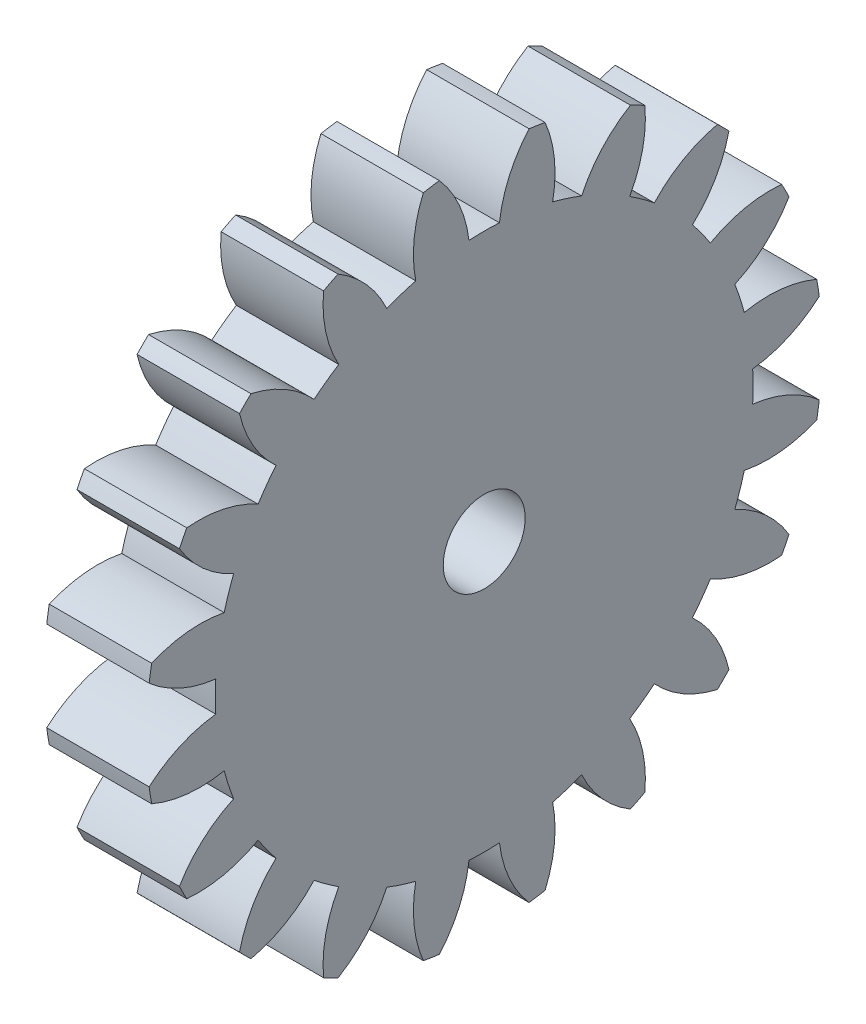
SolidWorks part; units mm, degrees
ref_plane "Plane1" through (0, 0, 0) normal (0, 0, 1) x (1, 0, 0)
ref_plane "Plane2" through (0, 0, 0) normal (0, 1, 0) x (1, 0, 0)
ref_plane "Plane3" through (0, 0, 0) normal (1, 0, 0) x (0, 0, -1)
other "Configuration Table"
sketch "HoldingSke" plane through (0, 0, 0) normal (0, 1, 0) x (1, 0, 0)
  line L0 (0, 0) -> (0.6265, -0.228)
  line L1 (-15, 0) -> (100, 0) construction
  line L2 (0, 0) -> (-2.1039, 2.3779)
  line L3 (0, 0) -> (-11.863, 4.5341)
  line L4 (0, 0) -> (8.1152, 2.9537)
  line L5 (0, 0) -> (-46.8476, -17.4728)
  line L6 (0, 0) -> (-4.1448, -2.7965)
  line L7 (-2.1039, 2.3779) -> (8.6586, 51.2059)
  line L8 (-76.2, 54.61) -> (-75.5, 54.61)
  line L9 (-71.009, 38.7566) -> (-53.1078, 45.2721)
  line L10 (-76.2, 71.12) -> (104.1128, 71.12)
  line L11 (0, 0) -> (-5, 0)
  line L12 (-76.2, 101.6) -> (-76.147, 101.6)
  line L13 (24.9733, 27.94) -> (52.9518, 28.4284)
  line L14 (24.9733, 27.94) -> (24.9743, 27.94)
  line L15 (24.9733, 27.94) -> (100.4006, 29.5858)
  line L16 (-63.627, -1.5) -> (-12.827, -1.5)
  circle A0 centre (0, 0) radius 2
  circle A1 centre (0, 0) radius 13.124
  circle A2 centre (0, 0) radius 37.5
  circle A3 centre (0, 0) radius 2
  dimension "MHD" = 26.248
  dimension "Hub_dia" = 75
  dimension "Bore" = 4
  dimension "MBD" = 4
  dimension "Num_teeth" = 20
  dimension "Pitch" = 0.6667
  dimension "Overall_len" = 50
  dimension "Show_teeth" = 20
  dimension "Thickness" = 5
  dimension "OAL" = 50.0001
  dimension "T_dim" = 0.7
  dimension "Ap" = 20
  dimension "H" = 19.05
  dimension "Pitch_radius" = 180.3128
  dimension "Width" = 5
  dimension "Backlash" = 0.053
  dimension "Addendum_fac" = 1
  dimension "Dedendum_fac" = 1.25
  dimension "Clearance_fac" = 0.25
  dimension "Dedendum_add" = 0.001
  dimension "Module" = 1.5
sketch "BasProSke" plane through (0, 0, 0) normal (0, 1, 0) x (1, 0, 0)
  line L0 (-10, 0) -> (60, 0) construction
  line L1 (0, 0) -> (0, 16.5)
  line L2 (0, 0) -> (5, 0)
  line L3 (5, 0) -> (5, 16.5)
  line L4 (5, 16.5) -> (0, 16.5)
  dimension "Thickness" = 5
  dimension "Diameter" = 33
revolve "Base-Revolve" add sketch "BasProSke" angle 360 about L0
sketch "TooCutSke" plane through (0, 0, 0) normal (1, 0, 0) x (0, 0, -1)
  line L1 (0, 0) -> (0, 107) construction
  line L2 (0, 0) -> (-1.2696, 14.9462) construction
  line L3 (0, 0) -> (-4.6808, 29.5532) construction
  line L4 (-1.2696, 14.9462) -> (-2.3404, 14.7766) construction
  arc A0 (0.7438, 13.1029) -> (-0.7438, 13.1029) centre (0, 0) ccw
  arc A1 (2.21, 16.377) -> (-2.21, 16.377) centre (0, 0) ccw
  circle A2 centre (0, 0) radius 15 construction
  circle A3 centre (0, 0) radius 14.0954 construction
  arc A4 (-0.7438, 13.1029) -> (-2.21, 16.377) centre (-6.7025, 12.3999) ccw
  arc A5 (2.21, 16.377) -> (0.7438, 13.1029) centre (6.7025, 12.3999) ccw
  dimension "Root_dia" = 26.248
  dimension "Overcut_dia" = 33.0508
  dimension "Pitch_dia" = 30
  dimension "Base_dia" = 28.1908
  dimension "Flank_rad" = 6
  dimension "Half_ang" = 9
  dimension "Half_CT" = 1.0841
extrude "ToothCut" cut sketch "TooCutSke" along normal through all
fillet "Breaks" [suppressed] radius 0.03
fillet "RootFillets" [suppressed] radius 0.376
pattern_circular "TeethCuts" count 20 every 18 about axis through (-10, 0, 0) along (1, 0, 0) of "ToothCut", "RootFillets", "Breaks"
sketch "HubNeaOneSke" plane through (0, 0, 0) normal (-1, 0, 0) x (0, 0, 1)
  circle A0 centre (0, 0) radius 13.124
  dimension "Diameter" = 26.248
extrude "HubNearOne" [suppressed] add sketch "HubNeaOneSke" along normal blind 45.0001
sketch "HubNeaBotSke" plane through (0, 0, 0) normal (-1, 0, 0) x (0, 0, 1)
  circle A0 centre (0, 0) radius 13.124
  dimension "Diameter" = 26.248
extrude "HubNearBoth" [suppressed] add sketch "HubNeaBotSke" along normal blind 22.5
ref_plane "FarPln" through (5, 0, 0) normal (1, 0, 0) x (0, 0, -1)
sketch "HubFarSke" plane through (5, 0, 0) normal (1, 0, 0) x (0, 0, -1)
  circle A0 centre (0, 0) radius 13.124
  dimension "Diameter" = 26.248
extrude "HubFar" [suppressed] add sketch "HubFarSke" along normal blind 22.5
sketch "BorSke" plane through (0, 0, 0) normal (1, 0, 0) x (0, 0, -1)
  circle A0 centre (0, 0) radius 2
  dimension "Diameter" = 4
extrude "Bore" cut sketch "BorSke" along normal mid plane 100.0001
sketch "KeySke" plane through (0, 0, 0) normal (1, 0, 0) x (0, 0, -1)
  line L0 (-0.8, 0) -> (-0.8, 2.7)
  line L1 (-0.8, 2.7) -> (0.8, 2.7)
  line L2 (0.8, 2.7) -> (0.8, 0)
  line L3 (0, 0) -> (0, 34) construction
  line L4 (-0.8, 0) -> (0.8, 0)
  dimension "Offset" = 2.7
  dimension "Width" = 1.6
extrude "Keyway" [suppressed] cut sketch "KeySke" along normal mid plane 100.0001
pattern_circular "Keyway2" [suppressed] count 2 every 90 about axis through (-10, 0, 0) along (1, 0, 0)
equation "' \"Module@HoldingSke\" = 6.35"
equation "' \"Num_teeth@HoldingSke\" = 12"
equation "' \"Ap@HoldingSke\" =  20"
equation "' \"Ap@HoldingSke\" = 20"
equation "' \"Width@HoldingSke\" = 0.5 * 25.4"
equation "' \"Hub_dia@HoldingSke\"= 1 * 25.4"
equation "' \"Hub_dia@HoldingSke\" = 1 * 25.4"
equation "' \"Overall_len@HoldingSke\" = 1.0 * 25.4"
equation "' \"Bore@HoldingSke\" = 0.75 * 25.4"
equation "' \"T_dim@HoldingSke\" = 0.1 * 25.4"
equation "' \"Width@KeySke\" = 0.25 * 25.4"
equation "' \"Show_teeth@HoldingSke\" = 13"
equation "' \"Backlash@HoldingSke\" = 0.009 * 25.4"
equation "' \"Addendum_fac@HoldingSke\" = 1.0"
equation "' \"Dedendum_fac@HoldingSke\" = 1.25"
equation "' \"Dedendum_add@HoldingSke\" = 0.00005 * 25.4"
equation "' \"Clearance_fac@HoldingSke\" = 0.25"
equation "\"Pitch@HoldingSke\" = 1 / \"Module@HoldingSke\""
equation "\"Overcut_dia@TooCutSke\" = (\"Num_teeth@HoldingSke\" + 2 * \"Addendum_fac@HoldingSke\") / \"Pitch@HoldingSke\" + 0.002 * 25.4"
equation "\"Pitch_dia@TooCutSke\" = \"Num_teeth@HoldingSke\" / \"Pitch@HoldingSke\""
equation "\"Base_dia@TooCutSke\" = \"Num_teeth@HoldingSke\" / \"Pitch@HoldingSke\" * cos((\"Ap@HoldingSke\"  * 3.14159265 / 180))"
equation "\"Root_dia@TooCutSke\" = (\"Num_teeth@HoldingSke\" + 2) / \"Pitch@HoldingSke\" - 2 * (\"Addendum_fac@HoldingSke\" + \"Dedendum_fac@HoldingSke\") / \"Pitch@HoldingSke\" - \"Dedendum_add@HoldingSke\" * 2"
equation "\"Half_ang@TooCutSke\" = 180 / \"Num_teeth@HoldingSke\""
equation "\"Half_CT@TooCutSke\" = \"Num_teeth@HoldingSke\" / \"Pitch@HoldingSke\" * sin((3.14159265 / 2 / \"Num_teeth@HoldingSke\")) / 2 - 7 * \"Backlash@HoldingSke\" / 4"
equation "\"Flank_rad@TooCutSke\" = \"Num_teeth@HoldingSke\" / \"Pitch@HoldingSke\" / 5"
equation "\"Radius@RootFillets\" = \"Clearance_fac@HoldingSke\" / \"Pitch@HoldingSke\" + \"Dedendum_add@HoldingSke\""
equation "\"Break_rad@Breaks\" = 0.02 / \"Pitch@HoldingSke\""
equation "\"Thickness@HoldingSke\" = \"Width@HoldingSke\""
equation "\"OAL@HoldingSke\" = \"Thickness@HoldingSke\""
equation "\"MHD@HoldingSke\" = (\"Num_teeth@HoldingSke\" + 2) / \"Pitch@HoldingSke\" - 2 * (\"Addendum_fac@HoldingSke\" + \"Dedendum_fac@HoldingSke\")  / \"Pitch@HoldingSke\" - \"Dedendum_add@HoldingSke\" * 2"
equation "\"MBD@HoldingSke\" = (\"Num_teeth@HoldingSke\" + 2) / \"Pitch@HoldingSke\" - 2 * (\"Addendum_fac@HoldingSke\" + \"Dedendum_fac@HoldingSke\")  / \"Pitch@HoldingSke\" - \"Dedendum_add@HoldingSke\" * 2 - 0.002 * 25.4"
equation "\"MHD@HoldingSke\" = ((sgn( \"MHD@HoldingSke\" - \"Hub_dia@HoldingSke\" )-1)*( \"MHD@HoldingSke\" - \"Hub_dia@HoldingSke\" ))/-2+ \"Hub_dia@HoldingSke\""
equation "\"MBD@HoldingSke\" = ((sgn( \"MBD@HoldingSke\" - \"Bore@HoldingSke\" )-1)*( \"MBD@HoldingSke\" - \"Bore@HoldingSke\" ))/-2+ \"Bore@HoldingSke\""
equation "\"OAL@HoldingSke\" = ((sgn( \"OAL@HoldingSke\" - \"Overall_len@HoldingSke\" )+1)*( \"OAL@HoldingSke\" - \"Overall_len@HoldingSke\" ))/2 + \"Overall_len@HoldingSke\" + 0.000002 * 25.4"
equation "\"Num_teeth@TeethCuts\" = int( \"Show_teeth@HoldingSke\" ) + 1"
equation "\"Num_teeth@TeethCuts\" = ((sgn( \"Num_teeth@TeethCuts\" - \"Num_teeth@HoldingSke\" )-1)*( \"Num_teeth@TeethCuts\" - \"Num_teeth@HoldingSke\" ))/-2+ \"Num_teeth@HoldingSke\""
equation "\"Num_teeth@TeethCuts\" = ((sgn( \"Num_teeth@TeethCuts\" - 2.0)+1)*( \"Num_teeth@TeethCuts\" - 2.0))/2 +2.0"
equation "\"Angle@TeethCuts\" = 360.0 / \"Num_teeth@HoldingSke\""
equation "\"Diameter@BasProSke\" = (\"Num_teeth@HoldingSke\" + 2 * \"Addendum_fac@HoldingSke\") / \"Pitch@HoldingSke\""
equation "\"Thickness@BasProSke\"  = \"Thickness@HoldingSke\""
equation "' \"Fillet_rad@BasProSke\" =  \"Thickness@HoldingSke\" * 0.05"
equation "' \"Fillet_rad@BasProSke\" = \"Thickness@HoldingSke\" * 0.05"
equation "\"MHD@HoldingSke\" = ((sgn( \"MHD@HoldingSke\" - \"Root_dia@TooCutSke\" )-1)*( \"MHD@HoldingSke\" - \"Root_dia@TooCutSke\" ))/-2+ \"Root_dia@TooCutSke\""
equation "\"Diameter@HubNeaOneSke\" = \"MHD@HoldingSke\""
equation "\"Length@HubNearOne\" = \"OAL@HoldingSke\" - \"Thickness@BasProSke\""
equation "\"Diameter@HubNeaBotSke\" = \"MHD@HoldingSke\""
equation "\"Length@HubNearBoth\" = ( \"OAL@HoldingSke\" - \"Thickness@BasProSke\" ) / 2.0"
equation "\"Thickness@FarPln\" = \"Thickness@BasProSke\""
equation "\"Diameter@HubFarSke\" = \"MHD@HoldingSke\""
equation "\"Length@HubFar\" = ( \"OAL@HoldingSke\" - \"Thickness@BasProSke\" ) / 2.0"
equation "\"Diameter@BorSke\" = \"MBD@HoldingSke\""
equation "\"D1@Bore\" = \"OAL@HoldingSke\" * 2.0"
equation "\"D1@Keyway\" = \"OAL@HoldingSke\" * 2.0"
equation "\"Offset@KeySke\" = \"T_dim@HoldingSke\" + \"MBD@HoldingSke\" / 2.0"
